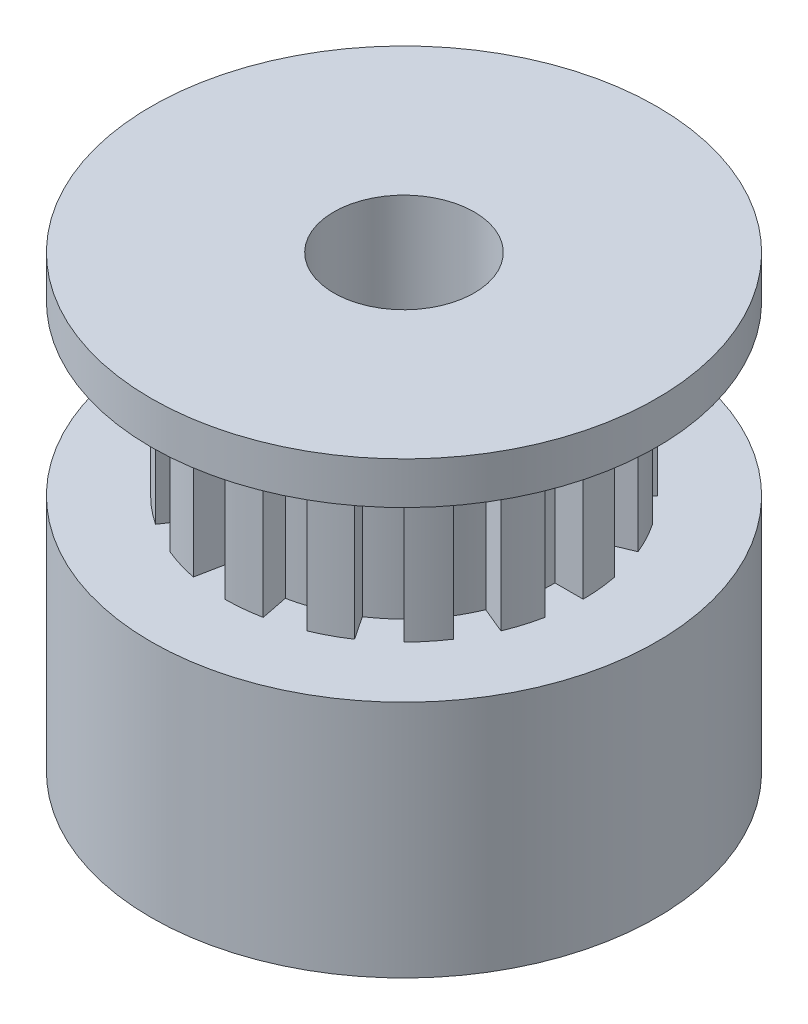
SolidWorks part; units mm, degrees
material "1060 Alloy"
ref_plane "Front Plane" through (0, 0, 0) normal (0, 0, 1) x (1, 0, 0)
ref_plane "Top Plane" through (0, 0, 0) normal (0, 1, 0) x (1, 0, 0)
ref_plane "Right Plane" through (0, 0, 0) normal (1, 0, 0) x (0, 0, -1)
sketch "Sketch1" plane through (0, 0, 0) normal (0, 0, 1) x (1, 0, 0)
  line L0 (-2.5, 0) -> (-2.5, 16)
  line L1 (-2.5, 16) -> (-9, 16)
  line L4 (-9, 16) -> (-9, 0)
  line L7 (-9, 0) -> (-2.5, 0)
  line L9 (0, 0) -> (0, 16) construction
  dimension "D1" = 5
  dimension "D2" = 18
  dimension "D3" = 16
revolve "Revolve1" add sketch "Sketch1" angle 360 about L9
sketch "Sketch2" plane through (0, 16, 0) normal (0, 1, 0) x (1, 0, 0)
  line L0 (0, 0) -> (0, -6.3764) construction
  line L1 (0, 0) -> (1.0489, -5.2731) construction
  line L2 (1.0489, -5.2731) -> (1.244, -6.2539)
  line L3 (0, 0) -> (2.0575, -4.9672) construction
  line L4 (2.0575, -4.9672) -> (2.4402, -5.8911)
  line L5 (0, -6.3764) -> (1.244, -6.2539) construction
  line L6 (2.4402, -5.8911) -> (1.244, -6.2539) construction
  line L7 (0, -6.3764) -> (0, -9)
  line L8 (3.4442, -8.3149) -> (2.4402, -5.8911)
  arc A0 (0, -6.3764) -> (1.244, -6.2539) centre (0, 0) ccw
  arc A1 (1.0489, -5.2731) -> (2.0575, -4.9672) centre (0, 0) ccw
  circle A2 centre (0, 0) radius 9 construction
  arc A3 (0, -9) -> (3.4442, -8.3149) centre (0, 0) ccw
  dimension "D1" = 1
  dimension "D2" = 1.25
  dimension "D3" = 22.5
extrude "Cut-Extrude1" cut sketch "Sketch2" against normal blind 6 from offset 1.5 offset against normal yes
pattern_circular "CirPattern1" count 16 over 360 about axis through (0, 0, 0) along (0, 1, 0) of "Cut-Extrude1"
